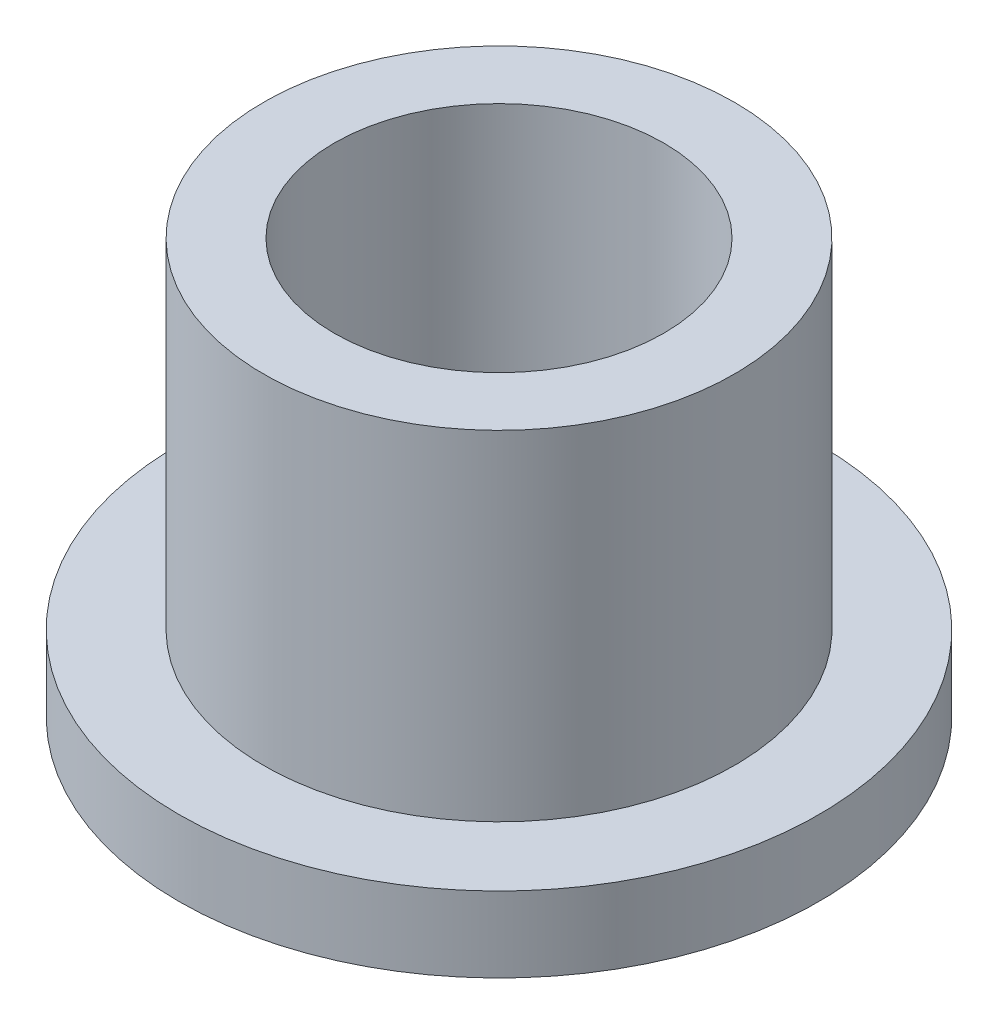
SolidWorks part; units mm, degrees
ref_plane "Front Plane" through (0, 0, 0) normal (0, 0, 1) x (1, 0, 0)
ref_plane "Top Plane" through (0, 0, 0) normal (0, 1, 0) x (1, 0, 0)
ref_plane "Right Plane" through (0, 0, 0) normal (1, 0, 0) x (0, 0, -1)
sketch "Sketch1" plane through (0, 0, 0) normal (0, 0, 1) x (1, 0, 0)
  line L0 (0, 0) -> (34, 0)
  line L1 (34, 0) -> (34, 8)
  line L2 (34, 8) -> (25, 8)
  line L3 (25, 8) -> (25, 44)
  line L4 (25, 44) -> (17.5, 44)
  line L5 (17.5, 44) -> (17.5, 0)
  line L6 (0, 0) -> (0, 44)
  line L9 (0, 44) -> (17.5, 44)
  dimension "D1" = 34
  dimension "D2" = 8
  dimension "D3" = 44
  dimension "D4" = 9
  dimension "D5" = 7.5
revolve "Revolve1" add sketch "Sketch1" angle 360 about L6
sketch "Sketch2" plane through (0, 44, 0) normal (0, 1, 0) x (1, 0, 0)
  circle A0 centre (0, 0) radius 17.5
extrude "Cut-Extrude1" cut sketch "Sketch2" against normal blind 50
